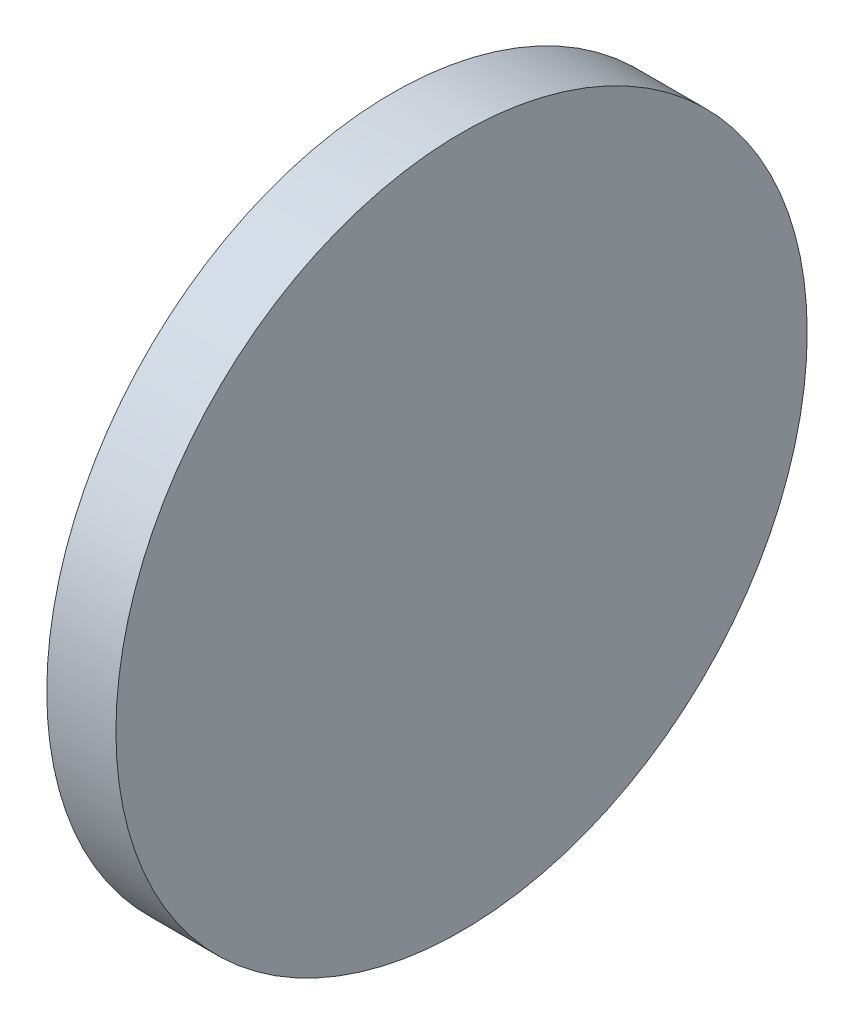
SolidWorks part; units mm, degrees
ref_plane "前视基准面" through (0, 0, 0) normal (0, 0, 1) x (1, 0, 0)
ref_plane "上视基准面" through (0, 0, 0) normal (0, 1, 0) x (1, 0, 0)
ref_plane "右视基准面" through (0, 0, 0) normal (1, 0, 0) x (0, 0, -1)
sketch "Sketch1" plane through (0, 0, 0) normal (1, 0, 0) x (0, 0, -1)
  circle A0 centre (0, 0) radius 50
  dimension "D1" = 100
extrude "Boss-Extrude1" add sketch "Sketch1" along normal blind 10
